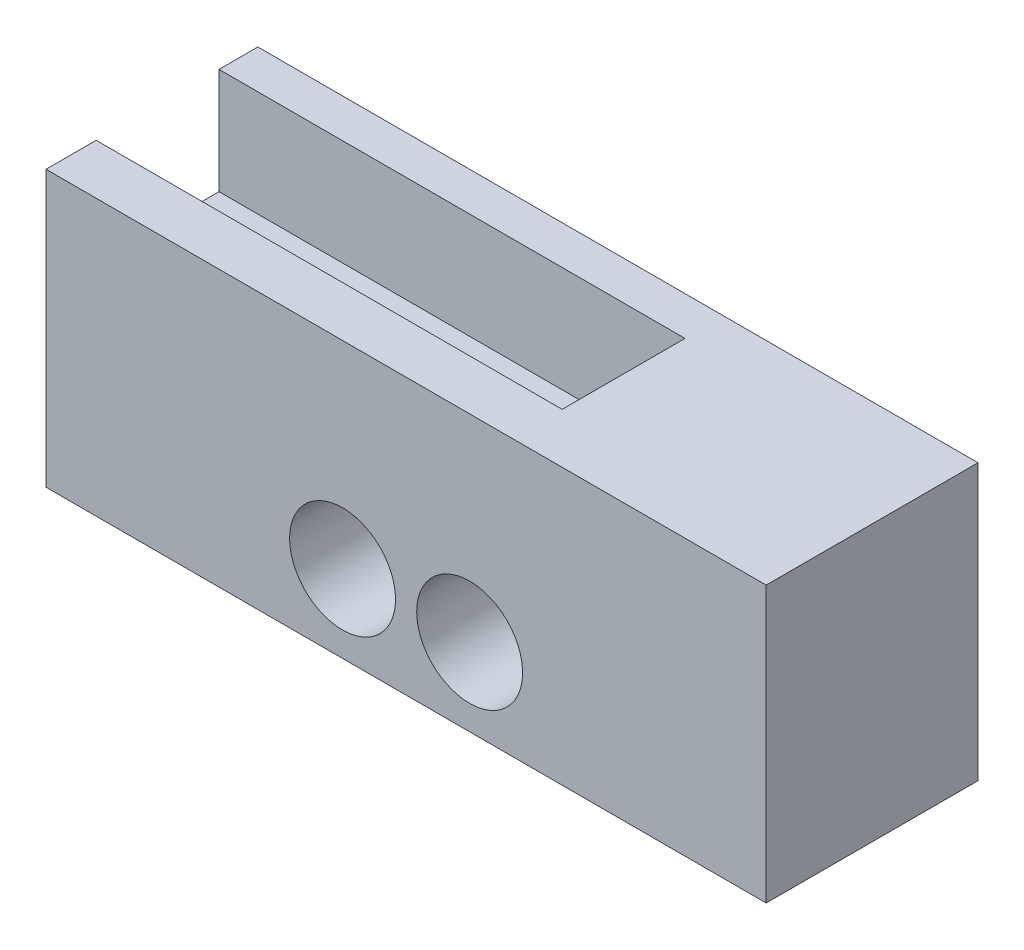
SolidWorks part; units mm, degrees
ref_plane "前基準面" through (0, 0, 0) normal (0, 0, 1) x (1, 0, 0)
ref_plane "上基準面" through (0, 0, 0) normal (0, 1, 0) x (1, 0, 0)
ref_plane "右基準面" through (0, 0, 0) normal (1, 0, 0) x (0, 0, -1)
sketch "草圖1" plane through (0, 0, 0) normal (0, 1, 0) x (1, 0, 0)
  line L1 (-16.2917, 6.1625) -> (17.7083, 6.1625)
  line L2 (-16.2917, 6.1625) -> (-16.2917, -3.8375)
  line L3 (-16.2917, -3.8375) -> (17.7083, -3.8375)
  line L4 (17.7083, 6.1625) -> (17.7083, -3.8375)
  line L5 (-16.2917, 6.1625) -> (17.7083, -3.8375) construction
  line L6 (-16.2917, -3.8375) -> (17.7083, 6.1625) construction
  point P4 (0.7083, 1.1625)
  dimension "D1" = 34
  dimension "D2" = 10
extrude "填料-伸長2" add sketch "草圖1" along normal blind 13
sketch "草圖2" plane through (0, 13, 0) normal (0, 1, 0) x (1, 0, 0)
  line L0 (-16.2917, 6.1625) -> (-16.2917, -3.8375) construction
  line L1 (-16.2917, 4.3309) -> (5.7083, 4.3309)
  line L2 (-16.2917, 4.3309) -> (-16.2917, -1.4691)
  line L3 (-16.2917, -1.4691) -> (5.7083, -1.4691)
  line L4 (5.7083, 4.3309) -> (5.7083, -1.4691)
  line M5 (-16.2917, 6.1625) -> (-16.2917, -3.8375)
  dimension "D1" = 22
  dimension "D2" = 5.8
extrude "除料-伸長1" cut sketch "草圖2" against normal blind 5 contours L4 L1 L3 M5
sketch "草圖3" plane through (0, 0, -6.1625) normal (0, 0, -1) x (-1, 0, 0)
  line L0 (16.2917, 13) -> (16.2917, 0) construction
  circle A0 centre (2.2917, 3.6632) radius 2.5
  circle A1 centre (-3.7083, 3.6632) radius 2.5
  point P10 (0, 0)
  point P11 (0, 0)
  dimension "D1" = 5
  dimension "D2" = 5
  dimension "D3" = 14
  dimension "D4" = 6
extrude "除料-伸長2" cut sketch "草圖3" against normal blind 20 contours A0 | A1
